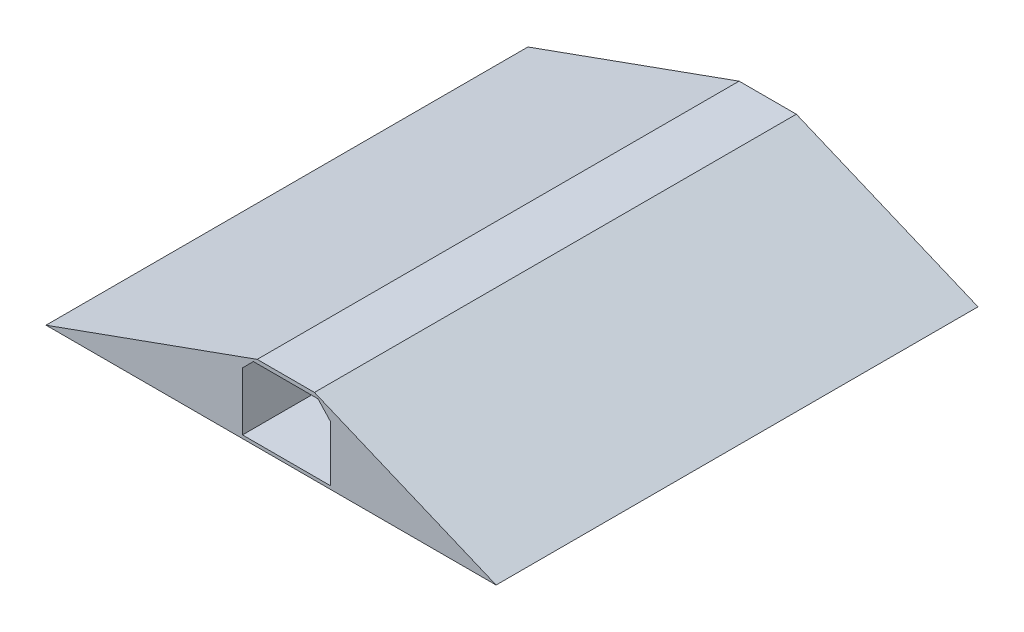
SolidWorks part; units mm, degrees
ref_plane "Alzado" through (0, 0, 0) normal (0, 0, 1) x (1, 0, 0)
ref_plane "Planta" through (0, 0, 0) normal (0, 1, 0) x (1, 0, 0)
ref_plane "Vista lateral" through (0, 0, 0) normal (1, 0, 0) x (0, 0, -1)
sketch "Croquis1" plane through (0, 0, 0) normal (0, 0, 1) x (1, 0, 0)
  line L3 (-7.0857, -21.054) -> (20.2874, -21.054)
  line L8 (-0.4446, -12.3799) -> (-6.9806, -12.3799)
  line L9 (-0.4446, -12.3799) -> (20.2874, -21.054)
  line L10 (-7.0857, -21.054) -> (-31.0857, -21.054)
  line L11 (-6.9806, -12.3799) -> (-31.0857, -21.054)
extrude "Saliente-Extruir1" add sketch "Croquis1" along normal blind 55
sketch "Croquis2" plane through (0, 0, 0) normal (0, 0, 1) x (1, 0, 0)
  line L0 (-7.4131, -12.8124) -> (-0.0414, -12.8124)
  line L2 (1.3793, -20.6879) -> (1.3793, -14.3364)
  line L3 (1.3793, -14.3364) -> (-0.0414, -12.8124)
  line L4 (-7.4131, -12.8124) -> (-8.6577, -14.0571)
  line L5 (-8.6577, -14.0571) -> (-8.6577, -20.6879)
  line L6 (-8.6577, -20.6879) -> (1.3793, -20.6879)
extrude "Cortar-Extruir1" cut sketch "Croquis2" along normal blind 68 contours L2 L3 L0 L4 L5 L6
